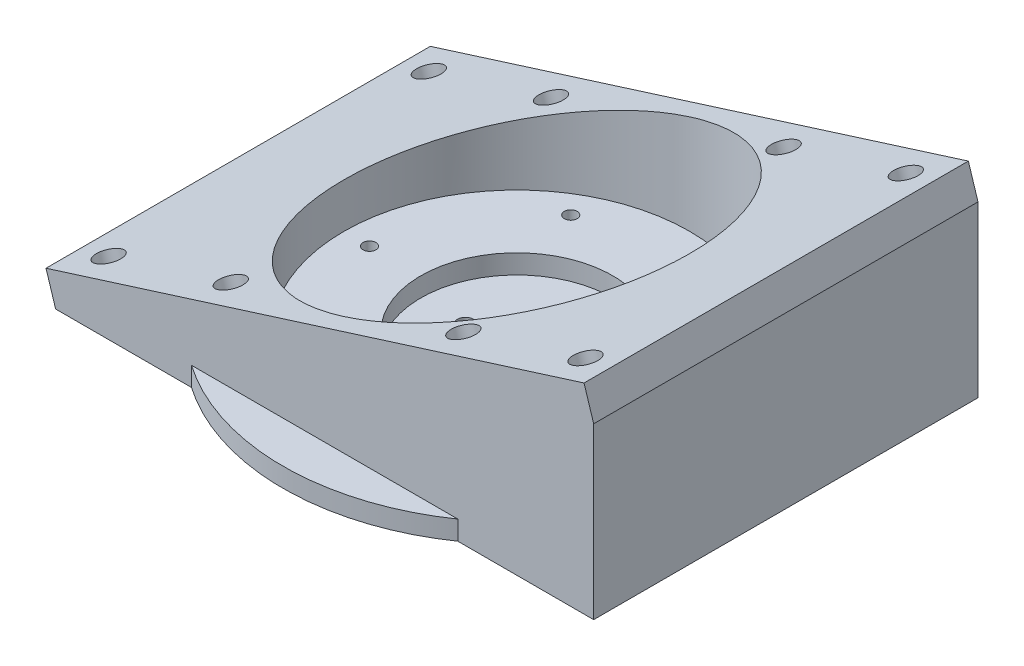
SolidWorks part; units mm, degrees
ref_plane "前视基准面" through (0, 0, 0) normal (0, 0, 1) x (1, 0, 0)
ref_plane "上视基准面" through (0, 0, 0) normal (0, 1, 0) x (1, 0, 0)
ref_plane "右视基准面" through (0, 0, 0) normal (1, 0, 0) x (0, 0, -1)
sketch "草图1" plane through (0, 0, 0) normal (0, 0, 1) x (1, 0, 0)
  line L0 (-67.0824, -7.9577) -> (16.9176, -7.9577)
  line L1 (16.9176, -7.9577) -> (16.9176, 18.5274)
  line L2 (-67.0824, -7.9577) -> (16.9176, 18.5274)
  dimension "D1" = 84
  dimension "D2" = 17.5
extrude "凸台-拉伸1" add sketch "草图1" along normal blind 60
sketch "草图2" plane through (-3.7837, 12.0003, 0) normal (-0.3007, 0.9537, 0) x (0.9537, 0.3007, 0)
  line L1 (-66.3705, 0) -> (21.7059, 0)
  line L2 (-66.3705, 0) -> (-66.3705, -60)
  line L3 (-66.3705, -60) -> (21.7059, -60)
  line L4 (21.7059, 0) -> (21.7059, -60)
extrude "凸台-拉伸2" add sketch "草图2" along normal blind 5
sketch "草图3" plane through (0, -7.9577, 0) normal (0, -1, 0) x (-1, 0, 0)
  line L0 (67.0824, -60) -> (67.0824, 0) construction
  line L2 (67.0824, -60) -> (-16.9176, -60) construction
  circle A0 centre (25.0824, -30) radius 27
  dimension "D1" = 42
  dimension "D2" = 30
extrude "切除-拉伸1" cut sketch "草图3" against normal blind 50
sketch "草图4" plane through (0, -7.9577, 0) normal (0, -1, 0) x (-1, 0, 0)
  circle A0 centre (25.0824, -30) radius 36.5
extrude "凸台-拉伸3" add sketch "草图4" against normal blind 3
sketch "草图13" plane through (0, -4.9577, 0) normal (0, 1, 0) x (1, 0, 0)
  circle A0 centre (-25.0824, -30) radius 20
  circle A1 centre (-25.0824, -30) radius 27 construction
  dimension "D1" = 0
extrude "切除-拉伸3" cut sketch "草图13" against normal blind 60
sketch "草图14" plane through (0, -4.9577, 0) normal (0, 1, 0) x (1, 0, 0)
  circle A0 centre (-48.0824, -30) radius 1
  circle A1 centre (-25.0824, -30) radius 20 construction
  dimension "D1" = 23
  dimension "D2" = 0
extrude "切除-拉伸4" cut sketch "草图14" against normal blind 60
pattern_circular "阵列(圆周)1" count 6 over 360 about axis through (-25.0824, 0, 30) along (0, 1, 0) of "切除-拉伸4"
sketch "草图16" plane through (-5.2872, 16.7689, 0) normal (-0.3007, 0.9537, 0) x (0.9537, 0.3007, 0)
  line L0 (21.7059, 0) -> (-66.3705, 0) construction
  line L1 (-66.3705, 0) -> (-66.3705, -60) construction
  line L2 (-66.3705, -60) -> (21.7059, -60) construction
  circle A0 centre (-61.3705, -5) radius 2
  circle A1 centre (-61.3705, -55) radius 2
  dimension "D1" = 5
  dimension "D3" = 5
  dimension "D2" = 5
  dimension "D4" = 5
extrude "切除-拉伸5" cut sketch "草图16" against normal blind 3
pattern_linear "阵列(线性)1" count 2 spacing 20 along (0.9537, 0.3007, 0) of "切除-拉伸5"
sketch "草图17" plane through (-5.2872, 16.7689, 0) normal (-0.3007, 0.9537, 0) x (0.9537, 0.3007, 0)
  line L0 (21.7059, -60) -> (21.7059, 0) construction
  line L1 (-66.3705, -60) -> (21.7059, -60) construction
  line L2 (21.7059, 0) -> (-66.3705, 0) construction
  circle A0 centre (16.7059, -55) radius 2
  circle A1 centre (16.7059, -5) radius 2
  dimension "D1" = 5
  dimension "D3" = 5
  dimension "D2" = 5
  dimension "D4" = 5
extrude "切除-拉伸6" cut sketch "草图17" against normal blind 3
pattern_linear "阵列(线性)2" count 2 spacing 20 along (-0.9537, -0.3007, 0) of "切除-拉伸6"
sketch "草图18" plane through (0, -4.9577, 0) normal (0, 1, 0) x (1, 0, 0)
  circle A0 centre (-25.0824, -30) radius 20
extrude "凸台-拉伸4" add sketch "草图18" against normal blind 6
sketch "草图19" plane through (0, -4.9577, 0) normal (0, 1, 0) x (1, 0, 0)
  circle A0 centre (-25.0824, -30) radius 6
extrude "切除-拉伸7" cut sketch "草图19" against normal blind 6
sketch "草图20" plane through (0, -4.9577, 0) normal (0, 1, 0) x (1, 0, 0)
  circle A0 centre (-25.0824, -30) radius 15
extrude "切除-拉伸8" cut sketch "草图20" against normal blind 3
sketch "草图21" plane through (0, -7.9577, 0) normal (0, 1, 0) x (1, 0, 0)
  circle A0 centre (-33.0824, -30) radius 1.25
  circle A1 centre (-25.0824, -30) radius 6 construction
  dimension "D1" = 0
  dimension "D2" = 8
extrude "切除-拉伸9" cut sketch "草图21" against normal blind 3
pattern_circular "阵列(圆周)2" count 4 over 360 about axis through (-25.0824, 0, 30) along (0, 1, 0) of "切除-拉伸9"
